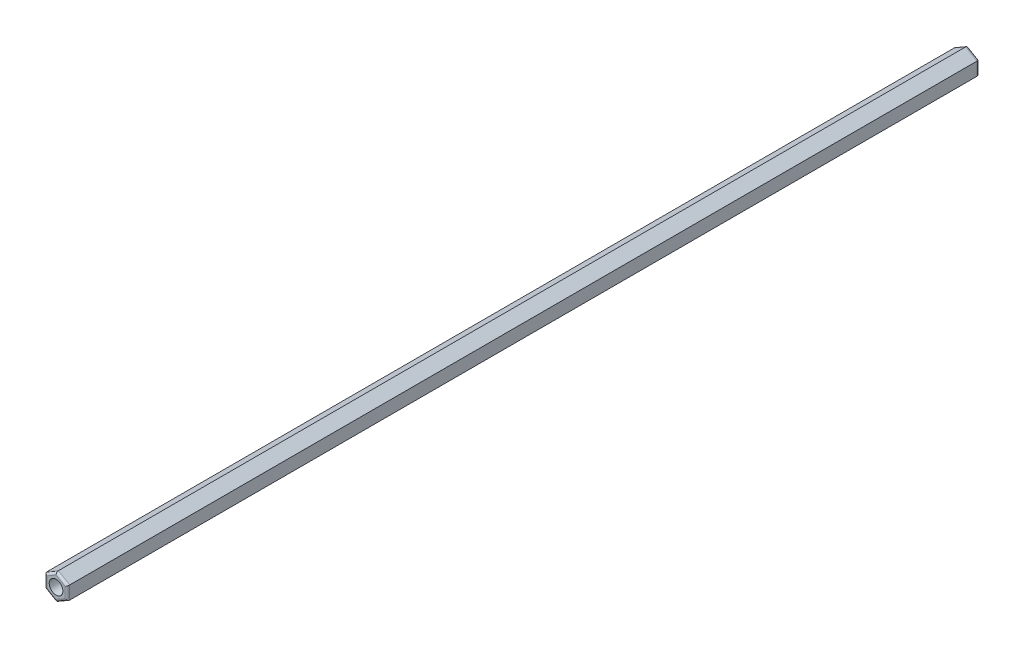
SolidWorks part; units mm, degrees
ref_plane "Plano frontal" through (0, 0, 0) normal (0, 0, 1) x (1, 0, 0)
ref_plane "Plano superior" through (0, 0, 0) normal (0, 1, 0) x (1, 0, 0)
ref_plane "Plano direito" through (0, 0, 0) normal (1, 0, 0) x (0, 0, -1)
ref_plane "Plano1" through (0, 0, 0) normal (0, 0, -1) x (-1, 0, 0)
sketch "Esboço1" plane through (0, 0, 0) normal (0, 0, -1) x (-1, 0, 0)
  line L0 (67.5021, -1.4434) -> (70.0021, -2.8868)
  line L1 (70.0021, -2.8868) -> (72.5021, -1.4434)
  line L2 (72.5021, -1.4434) -> (72.5021, 1.4434)
  line L3 (72.5021, 1.4434) -> (70.0021, 2.8868)
  line L4 (70.0021, 2.8868) -> (67.5021, 1.4434)
  line L5 (67.5021, 1.4434) -> (67.5021, -1.4434)
extrude "Ressalto-extrusão1" add sketch "Esboço1" against normal blind 200
fillet "Filete1" radius 0.5 12 edges at (-71.2521, 2.1651, 0) (-72.5021, 0, 0) (-68.7521, 2.1651, 0) (-71.2521, -2.1651, 0) (-67.5021, 0, 0) (-68.7521, -2.1651, 0) (-71.2521, 2.1651, 200) (-72.5021, 0, 200) (-68.7521, 2.1651, 200) (-71.2521, -2.1651, 200) (-67.5021, 0, 200) (-68.7521, -2.1651, 200)
sketch "Esboço2" plane through (0, 0, 200) normal (0, 0, 1) x (1, 0, 0)
  circle A0 centre (-70.0021, 0) radius 1.5
  dimension "D1" = 3
extrude "Corte-extrusão1" cut sketch "Esboço2" against normal through all
